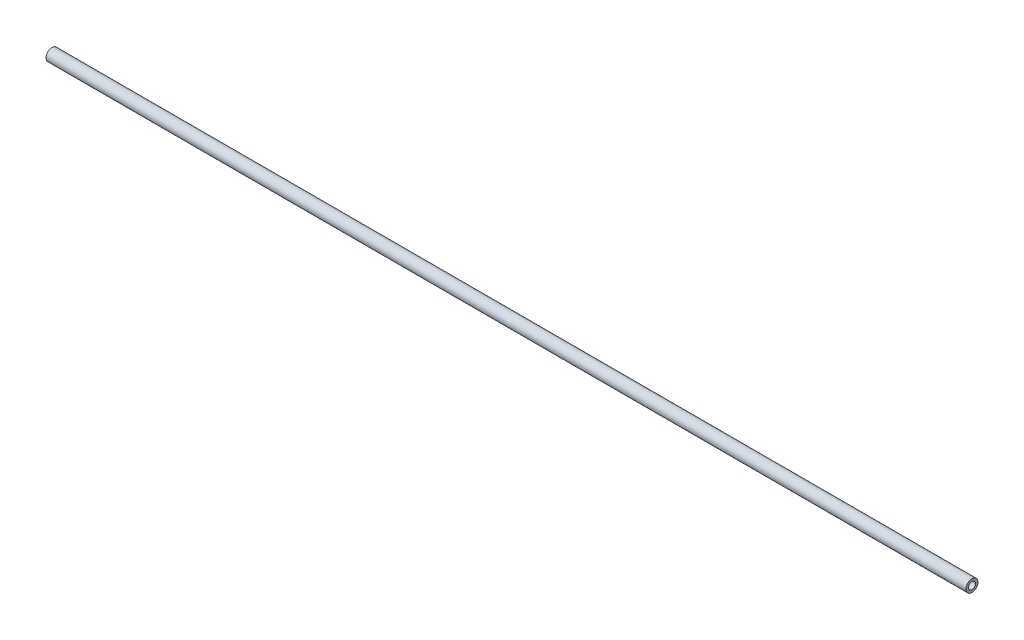
SolidWorks part; units mm, degrees
ref_plane "Front" through (0, 0, 0) normal (0, 0, 1) x (1, 0, 0)
ref_plane "Top" through (0, 0, 0) normal (0, 1, 0) x (1, 0, 0)
ref_plane "Right" through (0, 0, 0) normal (1, 0, 0) x (0, 0, -1)
sketch "Sketch1" plane through (0, 0, 0) normal (1, 0, 0) x (0, 0, -1)
  circle A0 centre (0, 0) radius 1.9844
  circle A1 centre (0, 0) radius 1.1906
  point P4 (1.9844, 0)
  point P5 (1.1906, 0)
  dimension "OD" = 3.9688
  dimension "ID" = 2.3813
  dimension "Wall" = 0.7937
extrude "Extrude1" add sketch "Sketch1" along normal mid plane 304.8
